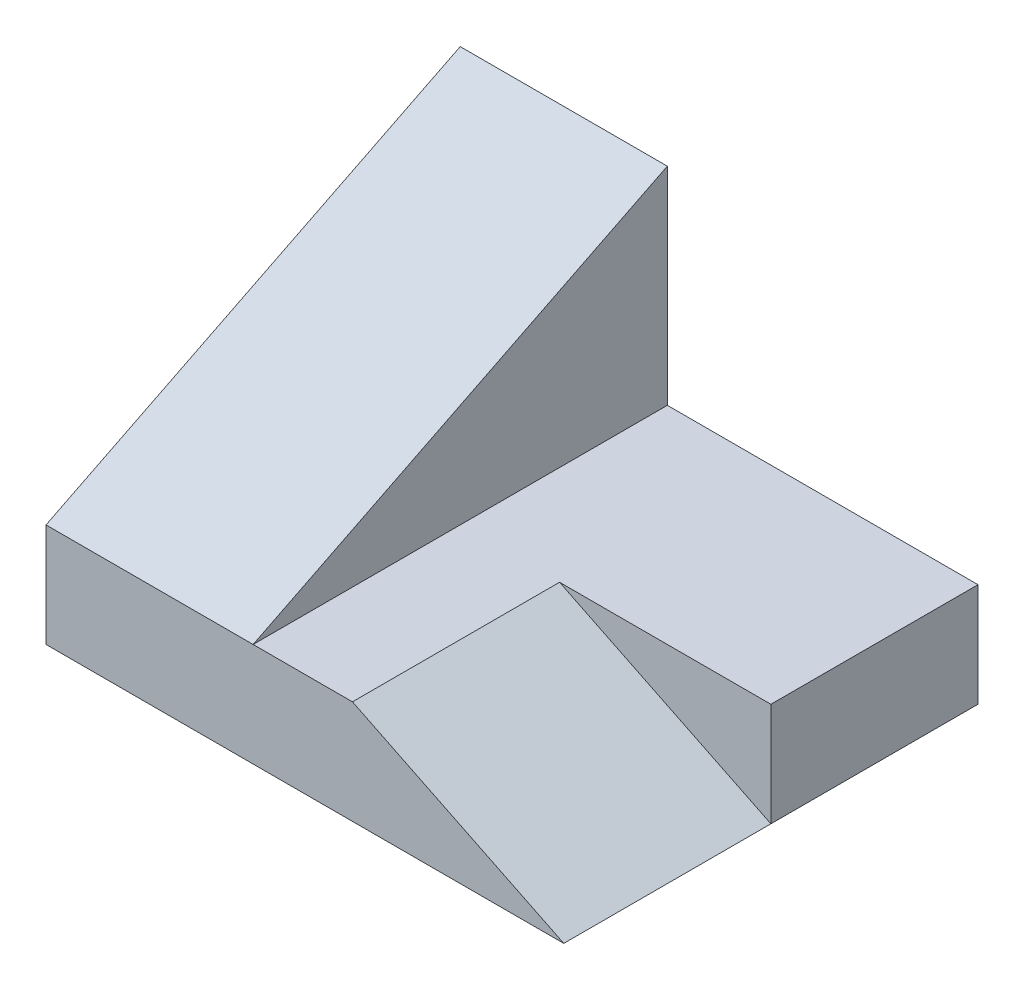
SolidWorks part; units mm, degrees
ref_plane "Front Plane" through (0, 0, 0) normal (0, 0, 1) x (1, 0, 0)
ref_plane "Top Plane" through (0, 0, 0) normal (0, 1, 0) x (1, 0, 0)
ref_plane "Right Plane" through (0, 0, 0) normal (1, 0, 0) x (0, 0, -1)
sketch "Sketch1" plane through (0, 0, 0) normal (0, 1, 0) x (1, 0, 0)
  line L1 (0, 0) -> (50, 0)
  line L2 (0, 0) -> (0, 40)
  line L3 (0, 40) -> (50, 40)
  line L4 (50, 0) -> (50, 40)
  dimension "D1" = 50
  dimension "D2" = 40
extrude "Boss-Extrude4" add sketch "Sketch1" along normal blind 10
sketch "Sketch8" plane through (0, 0, 0) normal (0, 0, 1) x (1, 0, 0)
  line L0 (50, 0) -> (50, 10)
  line L1 (50, 10) -> (29.5929, 10)
  line L2 (0, 10) -> (50, 10) construction
  line L3 (29.5929, 10) -> (50, 0)
extrude "Cut-Extrude1" cut sketch "Sketch8" against normal blind 20
sketch "Sketch9" plane through (0, 10, 0) normal (0, 1, 0) x (1, 0, 0)
  line L0 (0, 40) -> (20, 40)
  line L1 (50, 40) -> (0, 40) construction
  line L2 (20, 40) -> (20, 0)
  line L3 (0, 0) -> (29.5929, 0) construction
  line L4 (20, 0) -> (0, 0)
  line L5 (0, 0) -> (0, 40)
  dimension "D1" = 20
extrude "Boss-Extrude5" add sketch "Sketch9" along normal blind 20
sketch "Sketch10" plane through (0, 0, 0) normal (-1, 0, 0) x (0, 0, 1)
  line L0 (-40, 30) -> (0, 30)
  line L1 (0, 30) -> (0, 10)
  line L2 (0, 10) -> (-40, 30)
extrude "Cut-Extrude3" cut sketch "Sketch10" against normal blind 20
